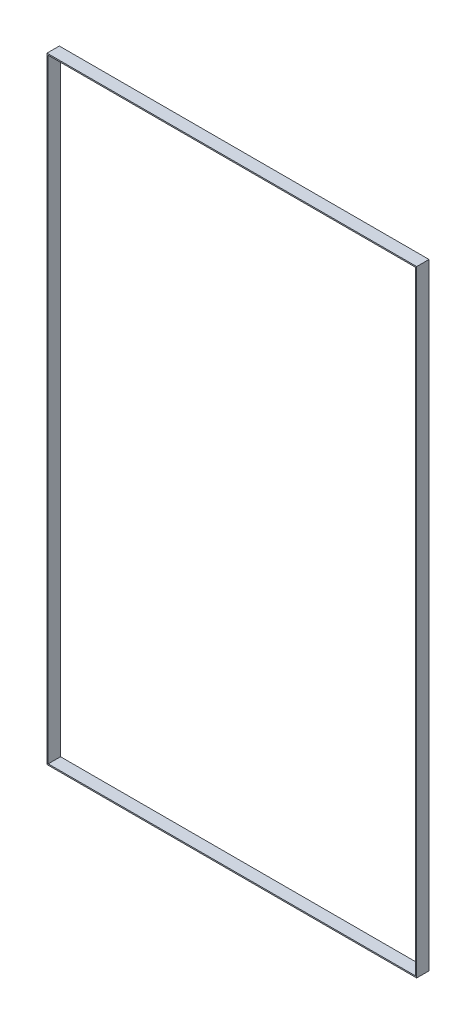
SolidWorks part; units mm, degrees
ref_plane "Front Plane" through (0, 0, 0) normal (0, 0, 1) x (1, 0, 0)
ref_plane "Top Plane" through (0, 0, 0) normal (0, 1, 0) x (1, 0, 0)
ref_plane "Right Plane" through (0, 0, 0) normal (1, 0, 0) x (0, 0, -1)
sketch "Sketch1" plane through (0, 0, 0) normal (0, 0, 1) x (1, 0, 0)
  line L1 (300, -500) -> (-300, -500)
  line L2 (300, -500) -> (300, 500)
  line L3 (300, 500) -> (-300, 500)
  line L4 (-300, -500) -> (-300, 500)
  line L5 (300, -500) -> (-300, 500) construction
  line L6 (300, 500) -> (-300, -500) construction
  line L7 (298, -498) -> (-298, -498)
  line L8 (298, -498) -> (298, 498)
  line L9 (298, 498) -> (-298, 498)
  line L10 (-298, -498) -> (-298, 498)
  line L11 (298, -498) -> (-298, 498) construction
  line L12 (298, 498) -> (-298, -498) construction
  point P0 (0, 0)
  point P6 (0, 0)
  dimension "D1" = 600
  dimension "D2" = 1000
  dimension "D3" = 596
  dimension "D4" = 996
extrude "Boss-Extrude1" add sketch "Sketch1" along normal blind 20
